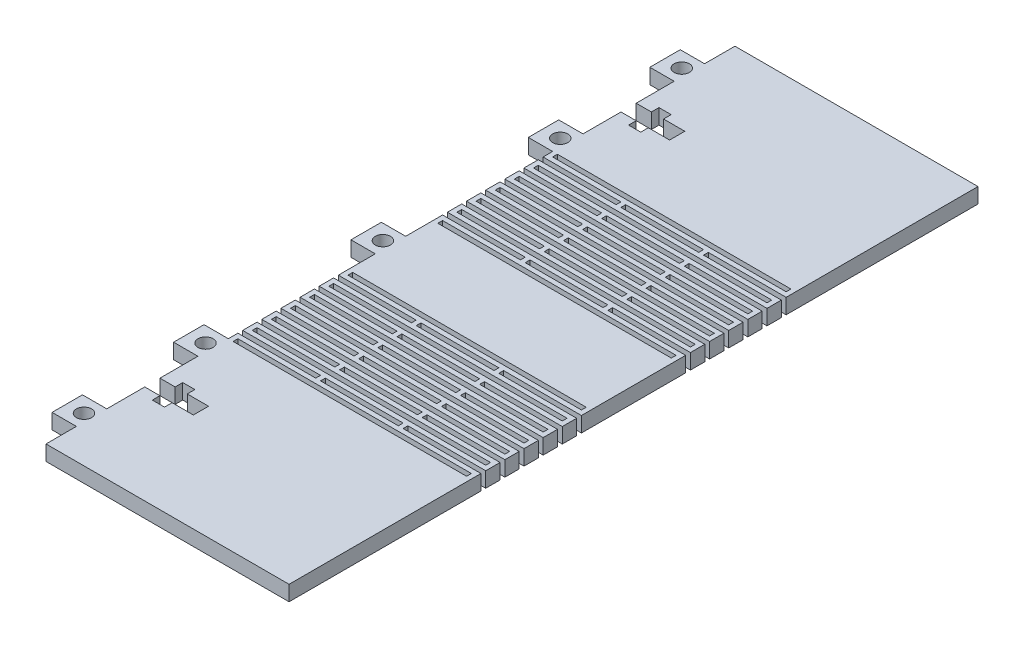
SolidWorks part; units mm, degrees
material "Acrylic (Medium-high impact)"
ref_plane "Front Plane" through (0, 0, 0) normal (0, 0, 1) x (1, 0, 0)
ref_plane "Top Plane" through (0, 0, 0) normal (0, 1, 0) x (1, 0, 0)
ref_plane "Right Plane" through (0, 0, 0) normal (1, 0, 0) x (0, 0, -1)
sketch "Sketch1" plane through (0, 0, 0) normal (0, 1, 0) x (1, 0, 0)
  line L1 (-25.4, 19.05) -> (25.4, 19.05)
  line L2 (-25.4, 19.05) -> (-25.4, -19.05)
  line L3 (-25.4, -19.05) -> (25.4, -19.05)
  line L4 (25.4, 19.05) -> (25.4, -19.05)
  line L5 (-25.4, 19.05) -> (25.4, -19.05) construction
  line L6 (-25.4, -19.05) -> (25.4, 19.05) construction
  point P0 (0, 0)
  dimension "D1" = 50.8
  dimension "D2" = 38.1
extrude "Boss-Extrude1" add sketch "Sketch1" along normal blind 3.175
sketch "Sketch2" plane through (0, 3.175, 0) normal (0, 1, 0) x (1, 0, 0)
  line L0 (-25.4, 12.7) -> (-30.48, 12.7)
  line L1 (-25.4, 19.05) -> (-25.4, -19.05) construction
  line L2 (-30.48, 12.7) -> (-30.48, 6.35)
  line L3 (-30.48, 6.35) -> (-25.4, 6.35)
  line L4 (-25.4, 6.35) -> (-25.4, 12.7)
  line L5 (25.4, 19.05) -> (-25.4, 19.05) construction
  dimension "D1" = 6.35
  dimension "D2" = 6.35
  dimension "D3" = 5.08
extrude "Boss-Extrude2" add sketch "Sketch2" against normal up to surface (3.175 mm away) up to face at (0, 0, 0)
sketch "Sketch3" plane through (0, 3.175, 0) normal (0, 1, 0) x (1, 0, 0)
  line L0 (-30.48, 9.525) -> (-26.9875, 9.525) construction
  line L1 (-30.48, 12.7) -> (-30.48, 6.35) construction
  line L2 (-25.4, 12.7) -> (-25.4, 9.525) construction
  line L4 (-26.9875, 9.525) -> (-25.4, 9.525) construction
  circle A0 centre (-26.9875, 9.525) radius 1.5875
  point P7 (-28.024, 9.525)
  point P8 (0, 0)
  point P11 (0, 0)
  point P12 (0, 0)
  point P13 (-25.6089, 9.525)
  dimension "D1" = 3.175
extrude "Cut-Extrude1" cut sketch "Sketch3" against normal through all
pattern_linear "LPattern1" count 2 spacing 25.4 along (0, 0, 1) of "Boss-Extrude2", "Cut-Extrude1"
sketch "Sketch11" plane through (0, 3.175, 0) normal (0, 1, 0) x (1, 0, 0)
  line L0 (-25.4, 6.35) -> (-25.4, -12.7) construction
  line L4 (-22.225, -1.5875) -> (-22.225, 0)
  line L5 (-22.225, 0) -> (-19.685, 0)
  line L6 (-19.685, 0) -> (-19.685, -1.5875)
  line L7 (-19.685, -1.5875) -> (-15.24, -1.5875)
  line L8 (-15.24, -1.5875) -> (-15.24, -4.7625)
  line L9 (-15.24, -4.7625) -> (-19.685, -4.7625)
  line L10 (-19.685, -4.7625) -> (-19.685, -6.35)
  line L11 (-19.685, -6.35) -> (-22.225, -6.35)
  line L12 (-22.225, -6.35) -> (-22.225, -4.7625)
  line L19 (-22.225, -1.5875) -> (-25.4, -1.5875)
  line L20 (-25.4, -1.5875) -> (-25.4, -4.7625)
  line L21 (-25.4, -4.7625) -> (-22.225, -4.7625)
  point P2 (-19.655, -3.175)
  point P3 (-24.2387, 0)
  point P4 (-25.4, -3.175)
  point P10 (-22.225, -4.7625)
  point P19 (-22.225, 0)
  point P20 (-22.225, -6.35)
  point P21 (-14.5742, -4.7625)
  dimension "D1" = 3.175
  dimension "D2" = 3.175
  dimension "D3" = 3.175
  dimension "D4" = 6.35
  dimension "D5" = 10.16
  dimension "D6" = 2.54
extrude "Cut-Extrude5" cut sketch "Sketch11" against normal through all
sketch "Sketch4" plane through (0, 3.175, 0) normal (0, 1, 0) x (1, 0, 0)
  line L0 (-25.4, -12.7) -> (-25.4, -19.05) construction
  line L1 (-30.48, -19.05) -> (25.4, -19.05) construction
  line L2 (-25.4, -19.05) -> (-25.4, -44.05)
  line L3 (-25.4, -44.05) -> (25.4, -44.05)
  line L4 (25.4, -44.05) -> (25.4, -19.05)
  line L5 (-25.4, -19.05) -> (25.4, -19.05)
  dimension "D1" = 25
extrude "Boss-Extrude3" add sketch "Sketch4" against normal up to surface (3.175 mm away) up to face at (-26.9875, 0, 17.4625)
sketch "Sketch5" plane through (0, 3.175, 0) normal (0, 1, 0) x (1, 0, 0)
  line L0 (-25.4, -19.05) -> (25.4, -19.05) construction
  line L1 (25.4, -44.05) -> (25.4, 19.05) construction
  line L2 (-24.4, -19.05) -> (24.4, -19.05)
  line L3 (24.4, -19.05) -> (24.4, -20.05)
  line L4 (24.4, -20.05) -> (-24.4, -20.05)
  line L5 (-24.4, -20.05) -> (-24.4, -19.05)
  line L6 (-25.4, -19.05) -> (-25.4, -44.05) construction
  line L8 (-25.4, -21.05) -> (-9.1333, -21.05)
  line L9 (-25.4, -21.05) -> (-25.4, -22.05)
  line L10 (-25.4, -22.05) -> (-9.1333, -22.05)
  line L11 (-9.1333, -21.05) -> (-9.1333, -22.05)
  line L12 (-8.1333, -21.05) -> (8.1333, -21.05)
  line L13 (-8.1333, -21.05) -> (-8.1333, -22.05)
  line L14 (-8.1333, -22.05) -> (8.1333, -22.05)
  line L15 (8.1333, -21.05) -> (8.1333, -22.05)
  line L16 (9.1333, -21.05) -> (25.4, -21.05)
  line L17 (9.1333, -21.05) -> (9.1333, -22.05)
  line L18 (9.1333, -22.05) -> (25.4, -22.05)
  line L19 (25.4, -21.05) -> (25.4, -22.05)
  point P9 (0, -19.05)
  point P24 (25.4, -24.6554)
  dimension "D1" = 1
  dimension "D2" = 1
  dimension "D3" = 1
  dimension "D4" = 1
  dimension "D5" = 1
  dimension "D6" = 1
  dimension "D7" = 1
  dimension "D8" = 1
  dimension "D9" = 1
  dimension "D10" = 1
extrude "Cut-Extrude2" cut sketch "Sketch5" against normal through all
pattern_linear "LPattern2" count 6 spacing 4 along (0, 0, 1) of "Cut-Extrude2"
sketch "Sketch6" plane through (0, 3.175, 0) normal (0, 1, 0) x (1, 0, 0)
  line L0 (-25.4, -30.05) -> (-25.4, -33.05) construction
  line L1 (-24.4, -43.05) -> (24.4, -43.05)
  line L2 (-24.4, -43.05) -> (-24.4, -44.05)
  line L3 (-24.4, -44.05) -> (24.4, -44.05)
  line L4 (24.4, -43.05) -> (24.4, -44.05)
  line L5 (25.4, -44.05) -> (25.4, -42.05) construction
  line L7 (-25.4, -44.05) -> (-24.4, -44.05) construction
  line L8 (-25.4, -44.05) -> (25.4, -44.05) construction
  point P10 (-23.4, -45.4166)
  dimension "D1" = 1
  dimension "D2" = 1
  dimension "D4" = 1
extrude "Cut-Extrude3" cut sketch "Sketch6" against normal through all
sketch "Sketch7" plane through (0, 3.175, 0) normal (0, 1, 0) x (1, 0, 0)
  line L0 (-25.4, -44.05) -> (25.4, -44.05)
  line L1 (25.4, -44.05) -> (25.4, -61.83)
  line L2 (25.4, -61.83) -> (-25.4, -61.83)
  line L3 (-25.4, -61.83) -> (-25.4, -44.05)
  dimension "D1" = 17.78
extrude "Boss-Extrude4" add sketch "Sketch7" against normal up to surface (3.175 mm away) up to face at (0, 0, 23.55)
sketch "Sketch8" plane through (0, 3.175, 0) normal (0, 1, 0) x (1, 0, 0)
  line L0 (-25.4, -49.765) -> (-30.48, -49.765)
  line L1 (-25.4, -30.05) -> (-25.4, -33.05) construction
  line L2 (-30.48, -49.765) -> (-30.48, -56.115)
  line L3 (-30.48, -56.115) -> (-25.4, -56.115)
  line L4 (-25.4, -56.115) -> (-25.4, -49.765)
  line L5 (-24.4, -44.05) -> (-25.4, -44.05) construction
  line L6 (-25.4, -44.05) -> (-25.4, -61.83) construction
  point P4 (-25.4, -56.9156)
  point P8 (-25.4, -52.94)
  dimension "D1" = 5.08
  dimension "D2" = 6.35
extrude "Boss-Extrude5" add sketch "Sketch8" against normal up to surface (3.175 mm away) up to face at (-6.5617, 0, 23.1036)
sketch "Sketch9" plane through (0, 3.175, 0) normal (0, 1, 0) x (1, 0, 0)
  line L0 (-25.4, -49.765) -> (-25.4, -52.94) construction
  line L2 (-30.48, -52.94) -> (-26.9875, -52.94) construction
  line L3 (-30.48, -56.115) -> (-30.48, -49.765) construction
  line L4 (-26.9875, -52.94) -> (-25.4, -52.94) construction
  circle A0 centre (-26.9875, -52.94) radius 1.5875
  point P3 (-27.7539, -52.94)
  point P10 (-25.7264, -52.94)
  dimension "D1" = 3.175
extrude "Cut-Extrude4" cut sketch "Sketch9" against normal through all
ref_plane "Plane1" through (0, 0, 52.94) normal (0, 0, -1) x (-1, 0, 0)
mirror "Mirror1" about plane through (0, 0, 52.94) normal (0, 0, -1) of "Boss-Extrude3", "Cut-Extrude2", "LPattern2", "Cut-Extrude3"
sketch "Sketch10" plane through (0, 3.175, 0) normal (0, 1, 0) x (1, 0, 0)
  line L0 (-25.4, -86.83) -> (25.4, -86.83)
  line L1 (25.4, -86.83) -> (25.4, -124.93)
  line L2 (25.4, -124.93) -> (-25.4, -124.93)
  line L3 (-25.4, -124.93) -> (-25.4, -86.83)
  dimension "D1" = 38.1
extrude "Boss-Extrude6" add sketch "Sketch10" against normal up to surface (3.175 mm away) up to face at (0, 0, 82.33)
mirror "Mirror3" about plane through (0, 0, 52.94) normal (0, 0, -1) of "Cut-Extrude5", "Boss-Extrude2", "Cut-Extrude1", "LPattern1"
